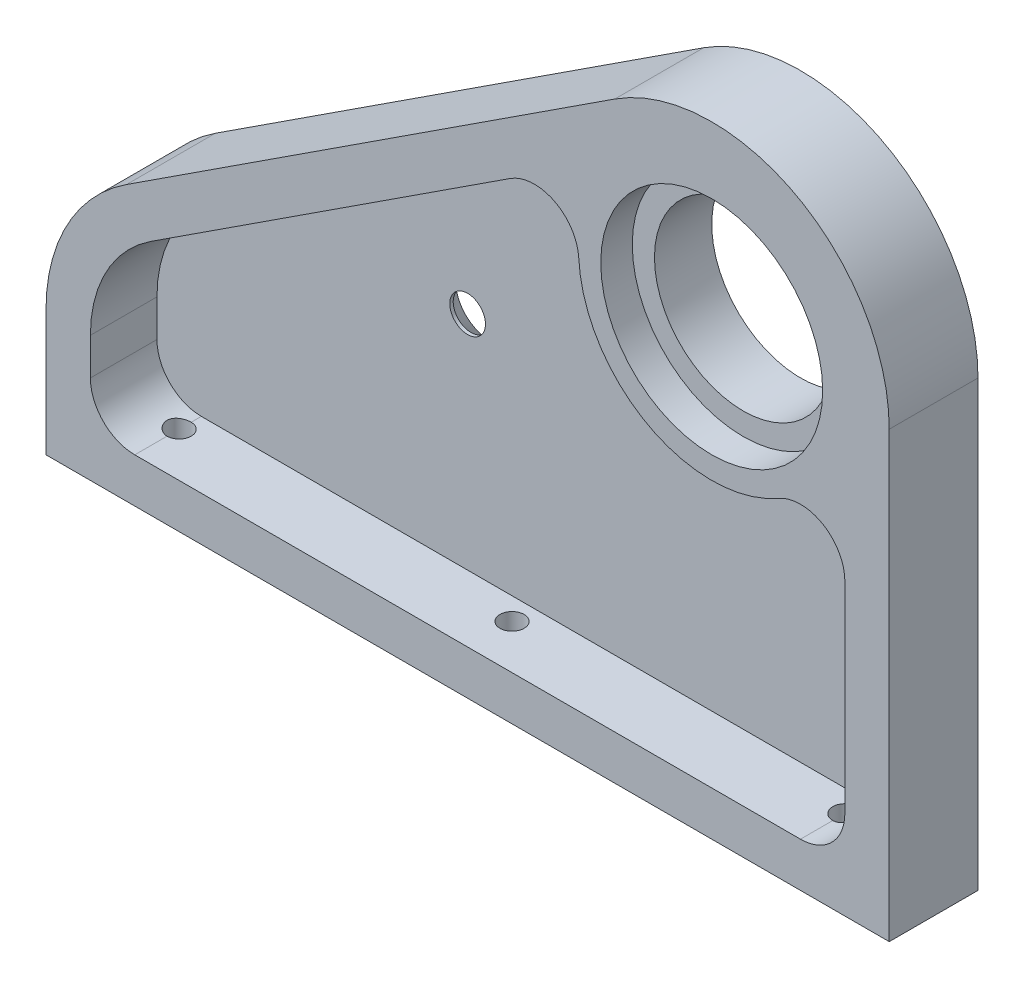
SolidWorks part; units mm, degrees
material "6061 Alloy"
ref_plane "Front Plane" through (0, 0, 0) normal (0, 0, 1) x (1, 0, 0)
ref_plane "Top Plane" through (0, 0, 0) normal (0, 1, 0) x (1, 0, 0)
ref_plane "Right Plane" through (0, 0, 0) normal (1, 0, 0) x (0, 0, -1)
sketch "Sketch1" plane through (0, 0, 0) normal (0, 0, 1) x (1, 0, 0)
  line L0 (25.4, 0) -> (25.4, -63.5)
  line L1 (25.4, -63.5) -> (-95.25, -63.5)
  line L2 (-95.25, -63.5) -> (-95.25, -31.75)
  line L3 (-13.8669, 21.2807) -> (-95.25, -31.75)
  arc A0 (25.4, 0) -> (-13.8669, 21.2807) centre (0, 0) ccw
  dimension "D1" = 50.8
  dimension "D2" = 63.5
  dimension "D4" = 31.75
  dimension "D5" = 120.65
extrude "Boss-Extrude1" add sketch "Sketch1" along normal mid plane 12.7
sketch "Sketch4" plane through (0, 0, 6.35) normal (0, 0, 1) x (1, 0, 0)
  circle A0 centre (0, 0) radius 12.7
  dimension "D1" = 25.4
extrude "Cut-Extrude3" cut sketch "Sketch4" against normal through all
sketch "Sketch5" plane through (0, 0, 6.35) normal (0, 0, -1) x (-1, 0, 0)
  circle A0 centre (0, 0) radius 15.875
  dimension "D1" = 31.75
extrude "Cut-Extrude4" cut sketch "Sketch5" along normal blind 4.5085
fillet "Fillet1" radius 25.4 1 edges at (-95.25, -31.75, 0)
sketch "Sketch9" plane through (0, 0, 6.35) normal (0, 0, 1) x (1, 0, 0)
  line L0 (-10.4002, 15.9605) -> (-80.2502, -29.555)
  line L1 (-88.9, -45.5155) -> (-88.9, -57.15)
  line L3 (19.05, -57.15) -> (19.05, 0)
  line L4 (-13.8669, 21.2807) -> (-83.7169, -24.2348)
  line L5 (-95.25, -45.5155) -> (-95.25, -63.5)
  line L6 (-95.25, -63.5) -> (25.4, -63.5)
  line L7 (25.4, -63.5) -> (25.4, 0)
  line L8 (-13.8669, 21.2807) -> (-83.7169, -24.2348) construction
  line L9 (-95.25, -45.5155) -> (-95.25, -63.5) construction
  line L10 (-95.25, -63.5) -> (25.4, -63.5) construction
  line L11 (25.4, -63.5) -> (25.4, 0) construction
  line L12 (-88.9, -57.15) -> (19.05, -57.15)
  line L13 (19.05, -57.15) -> (19.05, 0) construction
  line L14 (-88.9, -45.5155) -> (-88.9, -57.15) construction
  line L15 (-88.9, -57.15) -> (19.05, -57.15) construction
  arc A0 (-80.2502, -29.555) -> (-88.9, -45.5155) centre (-69.85, -45.5155) ccw
  arc A2 (-83.7169, -24.2348) -> (-95.25, -45.5155) centre (-69.85, -45.5155) ccw
  arc A3 (25.4, 0) -> (-13.8669, 21.2807) centre (0, 0) ccw
  arc A4 (-83.7169, -24.2348) -> (-95.25, -45.5155) centre (-69.85, -45.5155) ccw construction
  arc A5 (25.4, 0) -> (-13.8669, 21.2807) centre (0, 0) ccw construction
  arc A6 (-10.4002, 15.9605) -> (19.05, 0) centre (0, 0) ccw
  arc A7 (19.05, 0) -> (-10.4002, 15.9605) centre (0, 0) ccw construction
  dimension "D3" = 6.35
  dimension "D1" = 0
  dimension "D2" = 6.35
extrude "Cut-Extrude5" cut sketch "Sketch9" against normal offset from surface (9.525 mm away) 3.175 up to face at (12.7, 0, -6.35)
fillet "Fillet2" radius 6.35 4 edges at (-88.9, -57.15, 1.5875) (19.05, -57.15, 1.5875) (19.05, 0, 1.5875) (-10.4002, 15.9605, 1.5875)
hole_wizard "#8-32 Tapped Hole1" positions "Sketch8" profile "Sketch7" tap size "#8-32" standard "Ansi Inch"
sketch "Sketch8" plane through (0, -63.5, 0) normal (0, -1, 0) x (1, 0, 0)
  line L0 (12.7, 0) -> (-82.55, 0) construction
  line L4 (-95.25, 6.35) -> (25.4, 6.35) construction
  line L5 (-34.925, 6.35) -> (-34.925, 0) construction
  point P0 (-82.55, 0)
  point P7 (-34.925, 0)
  point P9 (12.7, 0)
  dimension "D1" = 95.25
sketch "Sketch7" plane through (-82.55, -63.5, 0) normal (1, 0, 0) x (0, 0, -1)
  line L0 (0, 0) -> (0, 11.7058)
  line L1 (0, 11.7058) -> (1.7272, 10.668)
  line L2 (1.7272, 10.668) -> (1.7272, 0)
  line L5 (1.7272, 0) -> (0, 0)
  line L10 (0, 11.7058) -> (-1.7272, 10.668) construction
  line L11 (0, -6.35) -> (0, 107.95) construction
  dimension "Tap Drill Dia." = 3.4544
  dimension "Tap Drill Depth" = 10.668
  dimension "Drill Angle" = 118
hole_wizard "CSK for #10 Flat Head Machine Screw1" positions "Sketch11" profile "Sketch10" countersink size "#10" standard "Ansi Inch" end condition through all
sketch "Sketch11" plane through (0, 0, -6.35) normal (0, 0, -1) x (-1, 0, 0)
  line L0 (95.25, -63.5) -> (-25.4, -63.5) construction
  line L1 (95.25, -45.5155) -> (95.25, -63.5) construction
  point P0 (44.45, -25.4)
  dimension "D1" = 38.1
  dimension "D2" = 50.8
sketch "Sketch10" plane through (-44.45, -25.4, -6.35) normal (1, 0, 0) x (0, 1, 0)
  line L0 (0, 0) -> (0, 12.7)
  line L1 (0, 12.7) -> (2.5527, 12.7)
  line L2 (2.5527, 12.7) -> (2.5527, 2.6882)
  line L3 (2.5527, 2.6882) -> (4.8895, 0)
  line L5 (4.8895, 0) -> (0, 0)
  line L6 (-2.5527, 2.6882) -> (-4.8895, 0) construction
  line L11 (0, -6.35) -> (0, 107.95) construction
  dimension "Thru Hole Dia." = 5.1054
  dimension "Thru Hole Depth" = 12.7
  dimension "Near C'Sink Dia." = 9.779
  dimension "Near C'Sink Angle" = 82
